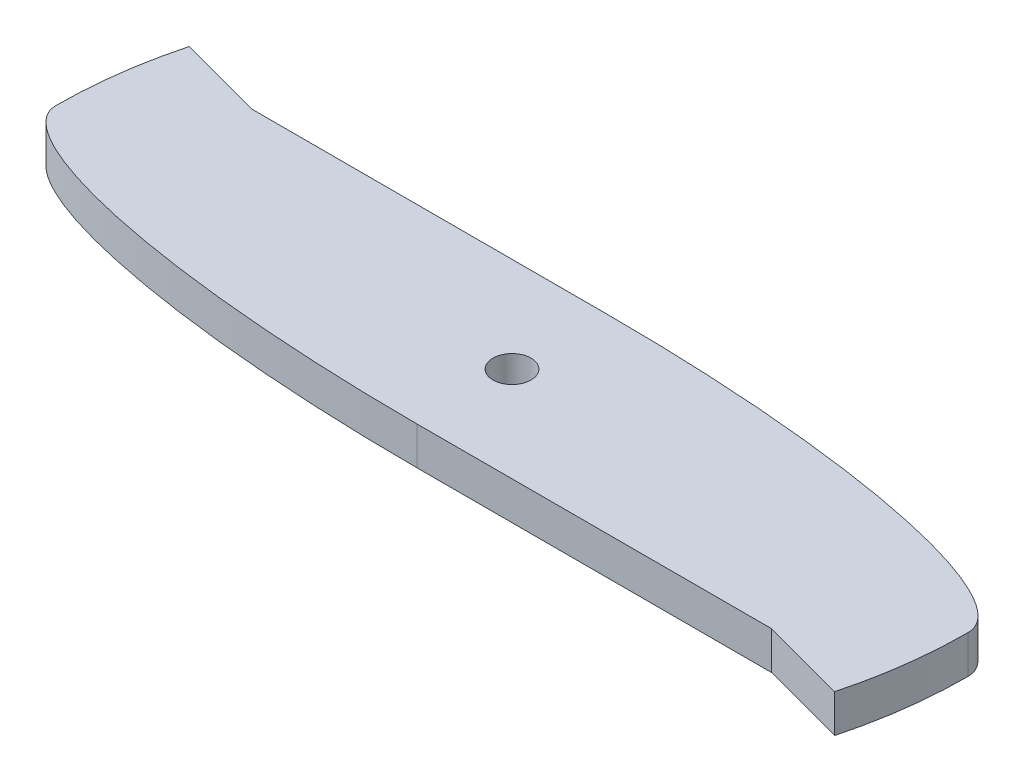
SolidWorks part; units mm, degrees
ref_plane "Front Plane" through (0, 0, 0) normal (0, 0, 1) x (1, 0, 0)
ref_plane "Top Plane" through (0, 0, 0) normal (0, 1, 0) x (1, 0, 0)
ref_plane "Right Plane" through (0, 0, 0) normal (1, 0, 0) x (0, 0, -1)
sketch "Sketch1" plane through (0, 0, 0) normal (0, 1, 0) x (1, 0, 0)
  line L0 (-76.2, 0) -> (76.2, 0) construction
  line L1 (73.6035, -19.722) -> (0, 0) construction
  line L2 (0, -15.875) -> (59.2463, -15.875)
  line L3 (59.2463, -15.875) -> (73.6035, -19.722)
  line L4 (-73.6035, 19.722) -> (0, 0) construction
  line L5 (0, 15.875) -> (-59.2463, 15.875)
  line L6 (-59.2463, 15.875) -> (-73.6035, 19.722)
  arc A0 (76.2, 0) -> (73.6035, -19.722) centre (0, 0) cw
  circle A1 centre (0, 0) radius 3.175
  circle A2 centre (0, 0) radius 15.875 construction
  arc A3 (-76.2, 0) -> (-73.6035, 19.722) centre (0, 0) cw
  ellipse E0 centre (0, 0) end of major axis (-76.2, 0) minor radius 15.875 (76.2, 0) -> (0, 15.875) ccw
  ellipse E1 centre (0, 0) end of major axis (76.2, 0) minor radius 15.875 (-76.2, 0) -> (0, -15.875) ccw
  point P4 (0, 0)
  dimension "D2" = 6.35
  dimension "D3" = 31.75
  dimension "D1" = 152.4
  dimension "D4" = 15
extrude "Boss-Extrude1" add sketch "Sketch1" along normal mid plane 6.35
